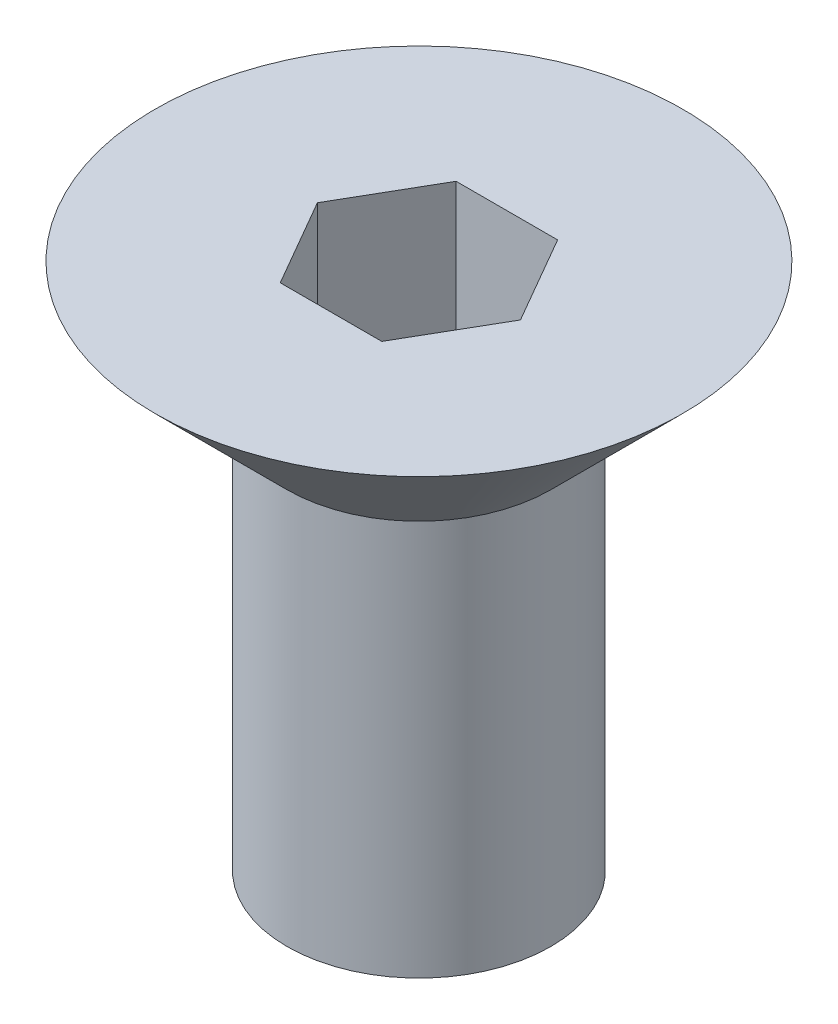
SolidWorks part; units mm, degrees
material "AISI 304"
ref_plane "Front Plane" through (0, 0, 0) normal (0, 0, 1) x (1, 0, 0)
ref_plane "Top Plane" through (0, 0, 0) normal (0, 1, 0) x (1, 0, 0)
ref_plane "Right Plane" through (0, 0, 0) normal (1, 0, 0) x (0, 0, -1)
sketch "Sketch1" plane through (0, 0, 0) normal (0, 0, 1) x (1, 0, 0)
  line L0 (0, 61.6916) -> (0, -59.3578) construction
  line L1 (0, -12) -> (3, -12)
  line L2 (3, -12) -> (3, -3)
  line L3 (-4.7326, -1.2674) -> (-3, -3) construction
  line L5 (6, 0) -> (0, 0)
  line L6 (0, 0) -> (0, -12)
  line L7 (3, -3) -> (6, 0)
  dimension "D1" = 90
  dimension "D2" = 12
  dimension "D3" = 6
  dimension "D5" = 12
revolve "Revolve1" add sketch "Sketch1" angle 360 about L0
sketch "Sketch2" plane through (0, 0, 0) normal (0, 1, 0) x (-1, 0, 0)
  line L1 (-1.1547, -2) -> (1.1547, -2)
  line L2 (1.1547, -2) -> (2.3094, 0)
  line L3 (2.3094, 0) -> (1.1547, 2)
  line L4 (1.1547, 2) -> (-1.1547, 2)
  line L5 (-1.1547, 2) -> (-2.3094, 0)
  line L6 (-2.3094, 0) -> (-1.1547, -2)
  circle A0 centre (0, 0) radius 2 construction
  dimension "D1" = 4
extrude "Cut-Extrude1" cut sketch "Sketch2" against normal blind 3
